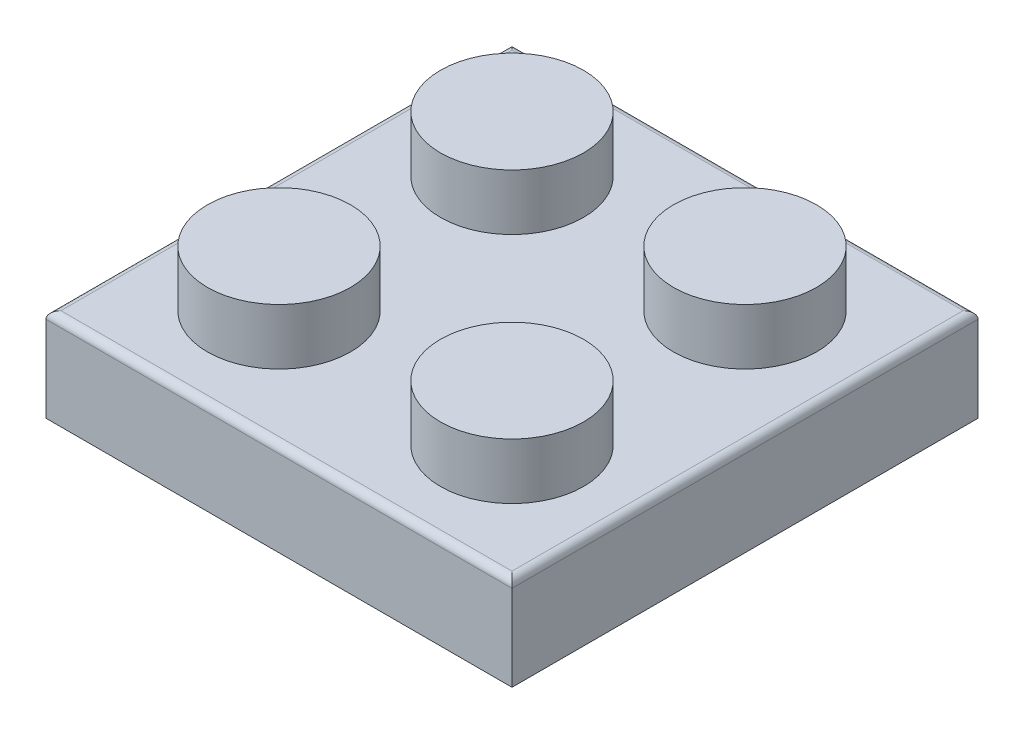
SolidWorks part; units mm, degrees
extrude "Base-Extrude" add sketch "Sketch1" along normal blind 3.175
sketch "Sketch1" plane through (0, 0, 0) normal (0, 1, 0) x (1, 0, 0)
  line L0 (0, 0) -> (0, 50.4571) construction
  line L1 (0, 0) -> (55.8847, 0) construction
  line L2 (-7.9375, 7.9375) -> (7.9375, 7.9375)
  line L3 (-7.9375, 7.9375) -> (-7.9375, -7.9375)
  line L4 (7.9375, -7.9375) -> (-7.9375, -7.9375)
  line L5 (7.9375, -7.9375) -> (7.9375, 7.9375)
  dimension "Length" = 15.875
  dimension "Width" = 15.875
ref_plane "Front" through (0, 0, 0) normal (0, 0, 1) x (1, 0, 0)
ref_plane "Top" through (0, 0, 0) normal (0, 1, 0) x (1, 0, 0)
ref_plane "Right" through (0, 0, 0) normal (1, 0, 0) x (0, 0, -1)
sketch "Sketch2" plane through (0, 3.175, 0) normal (0, 1, 0) x (-1, 0, 0)
  line L0 (7.9375, -7.9375) -> (7.9375, 7.9375) construction
  line L1 (-7.9375, 7.9375) -> (7.9375, 7.9375) construction
  circle A0 centre (3.9688, 3.9687) radius 2.4384
  dimension "DotDiam" = 4.8768
  dimension "DotLSpc" = 3.9688
  dimension "DotWSpc" = 3.9688
extrude "Boss-Extrude1" add sketch "Sketch2" along normal blind 1.905
pattern_linear "LPattern4" count 2 spacing 7.9375 along (1, 0, 0) count 2 spacing 7.9375 along (0, 0, -1) of "Boss-Extrude1"
shell "Shell1" thickness 1.5875
sketch "Sketch3" plane through (0, 1.5875, 0) normal (0, -1, 0) x (1, 0, 0)
  line L0 (-7.9375, -7.9375) -> (-7.9375, 7.9375) construction
  circle A0 centre (0, 0) radius 2.4384
extrude "InsDot" add sketch "Sketch3" along normal up to surface (1.5875 mm away) thin
pattern_linear "LPattern5" [suppressed]
sketch "Sketch4" plane through (0, 1.5875, 0) normal (0, -1, 0) x (1, 0, 0)
  line L0 (7.9375, 7.9375) -> (7.9375, -7.9375) construction
  circle A0 centre (0, 0) radius 1.27
extrude "InsDot2" [suppressed] add sketch "Sketch4" along normal up to surface (1.5875 mm away)
pattern_linear "LPattern6" [suppressed]
fillet "Fillet1" radius 0.254 4 edges at (7.9375, 3.175, 0) (0, 3.175, -7.9375) (-7.9375, 3.175, 0) (0, 3.175, 7.9375)
equation "\"InsDotPat@LPattern5\" = \"InsDotSpc@Sketch3\""
equation "\"WdotSpc@LPattern4\" = \"LdotSpc@LPattern4\""
equation "\"InsDot2Pat@LPattern6\" = \"InsDot2Spc@Sketch4\""
